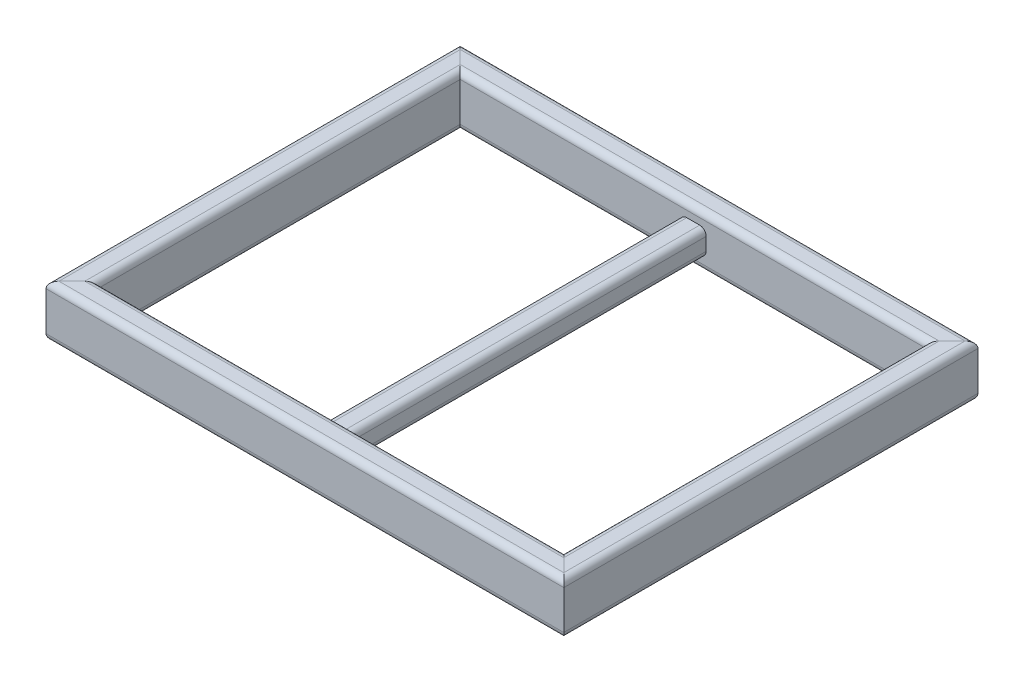
SolidWorks part; units mm, degrees
ref_plane "Front Plane" through (0, 0, 0) normal (0, 0, 1) x (1, 0, 0)
ref_plane "Top Plane" through (0, 0, 0) normal (0, 1, 0) x (1, 0, 0)
ref_plane "Right Plane" through (0, 0, 0) normal (1, 0, 0) x (0, 0, -1)
sketch "Sketch2" plane through (0, 0, 0) normal (0, 1, 0) x (1, 0, 0)
  line L0 (0, 406.4) -> (0, -406.4)
  line L1 (-508, -406.4) -> (508, -406.4)
  line L2 (-508, -406.4) -> (-508, 406.4)
  line L3 (-508, 406.4) -> (508, 406.4)
  line L4 (508, -406.4) -> (508, 406.4)
  line L5 (-508, -406.4) -> (508, 406.4) construction
  line L6 (-508, 406.4) -> (508, -406.4) construction
  point P0 (0, 0)
  dimension "D1" = 1016
  dimension "D2" = 812.8
other "Rectangular tube 4 X 2 X 0.25(1)"
ref_plane "Plane1" through (-482.6, 0, 406.4) normal (0, 0, -1) x (-1, 0, 0)
sketch "Sketch1" plane through (-482.6, 0, 406.4) normal (0, 0, -1) x (-1, 0, 0)
  line L0 (-12.7, -44.45) -> (12.7, -44.45)
  line L1 (-19.05, -38.1) -> (-19.05, 38.1)
  line L2 (12.7, 44.45) -> (-12.7, 44.45)
  line L3 (19.05, 38.1) -> (19.05, -38.1)
  line L4 (-12.7, -50.8) -> (12.7, -50.8)
  line L5 (-25.4, -38.1) -> (-25.4, 38.1)
  line L6 (12.7, 50.8) -> (-12.7, 50.8)
  line L7 (25.4, 38.1) -> (25.4, -38.1)
  line L8 (0, 0) -> (25.4, 0) construction
  line L9 (0, 0) -> (0, 50.8) construction
  arc A0 (25.4, 38.1) -> (12.7, 50.8) centre (12.7, 38.1) ccw
  arc A1 (12.7, -50.8) -> (25.4, -38.1) centre (12.7, -38.1) ccw
  arc A2 (-25.4, -38.1) -> (-12.7, -50.8) centre (-12.7, -38.1) ccw
  arc A3 (-12.7, 50.8) -> (-25.4, 38.1) centre (-12.7, 38.1) ccw
  arc A4 (-12.7, 44.45) -> (-19.05, 38.1) centre (-12.7, 38.1) ccw
  arc A5 (19.05, 38.1) -> (12.7, 44.45) centre (12.7, 38.1) ccw
  arc A6 (12.7, -44.45) -> (19.05, -38.1) centre (12.7, -38.1) ccw
  arc A7 (-19.05, -38.1) -> (-12.7, -44.45) centre (-12.7, -38.1) ccw
  point P3 (0, -50.8)
  point P4 (-25.4, 0)
  point P5 (0, 0)
  point P6 (25.4, -50.8)
  point P7 (-25.4, -50.8)
  point P8 (-25.4, 50.8)
  point P33 (0, 0)
  point P35 (25.4, 50.8)
  point P36 (25.4, 0)
  point P37 (0, 50.8)
  dimension "D1" = 12.7
  dimension "Thickness" = 6.35
  dimension "V_leg" = 101.6
  dimension "H_leg" = 50.8
other "Square tube 2 X 2 X 0.25(1)"
ref_plane "Plane2" through (0, 0, -406.4) normal (0, 0, 1) x (1, 0, 0)
sketch "Sketch11" plane through (0, 0, -406.4) normal (0, 0, 1) x (1, 0, 0)
  line L0 (-12.7, -19.05) -> (12.7, -19.05)
  line L1 (-19.05, -12.7) -> (-19.05, 12.7)
  line L2 (12.7, 19.05) -> (-12.7, 19.05)
  line L3 (19.05, 12.7) -> (19.05, -12.7)
  line L4 (-12.7, -25.4) -> (12.7, -25.4)
  line L5 (-25.4, -12.7) -> (-25.4, 12.7)
  line L6 (12.7, 25.4) -> (-12.7, 25.4)
  line L7 (25.4, 12.7) -> (25.4, -12.7)
  line L8 (0, 0) -> (19.05, 0) construction
  line L9 (0, 0) -> (0, 19.05) construction
  arc A0 (25.4, 12.7) -> (12.7, 25.4) centre (12.7, 12.7) ccw
  arc A1 (12.7, -25.4) -> (25.4, -12.7) centre (12.7, -12.7) ccw
  arc A2 (-25.4, -12.7) -> (-12.7, -25.4) centre (-12.7, -12.7) ccw
  arc A3 (-12.7, 25.4) -> (-25.4, 12.7) centre (-12.7, 12.7) ccw
  arc A4 (-12.7, 19.05) -> (-19.05, 12.7) centre (-12.7, 12.7) ccw
  arc A5 (19.05, 12.7) -> (12.7, 19.05) centre (12.7, 12.7) ccw
  arc A6 (12.7, -19.05) -> (19.05, -12.7) centre (12.7, -12.7) ccw
  arc A7 (-19.05, -12.7) -> (-12.7, -19.05) centre (-12.7, -12.7) ccw
  point P3 (0, 25.4)
  point P4 (25.4, 0)
  point P5 (0, -25.4)
  point P6 (-25.4, 0)
  point P7 (-25.4, 25.4)
  point P8 (-25.4, -25.4)
  point P33 (0, 0)
  point P35 (25.4, -25.4)
  point P36 (25.4, 25.4)
  point P37 (0, 0)
  dimension "D1" = 12.7
  dimension "Thickness" = 6.35
  dimension "V_leg" = 50.8
other "Trim/Extend1"
